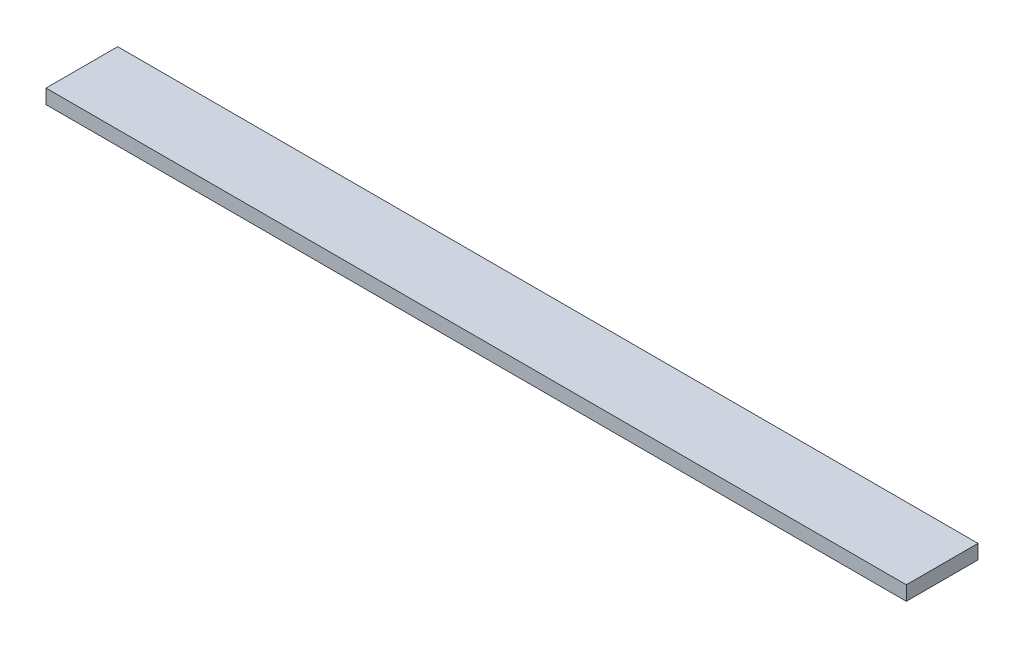
SolidWorks part; units mm, degrees
material "Silicon Rubber"
ref_plane "Front Plane" through (0, 0, 0) normal (0, 0, 1) x (1, 0, 0)
ref_plane "Top Plane" through (0, 0, 0) normal (0, 1, 0) x (1, 0, 0)
ref_plane "Right Plane" through (0, 0, 0) normal (1, 0, 0) x (0, 0, -1)
sketch "Sketch1" plane through (0, 0, 0) normal (0, 1, 0) x (1, 0, 0)
  line L1 (0, 0) -> (120, 0)
  line L2 (0, 0) -> (0, 10)
  line L3 (0, 10) -> (120, 10)
  line L4 (120, 0) -> (120, 10)
  dimension "D1" = 120
  dimension "D2" = 10
extrude "Boss-Extrude1" add sketch "Sketch1" along normal blind 2
